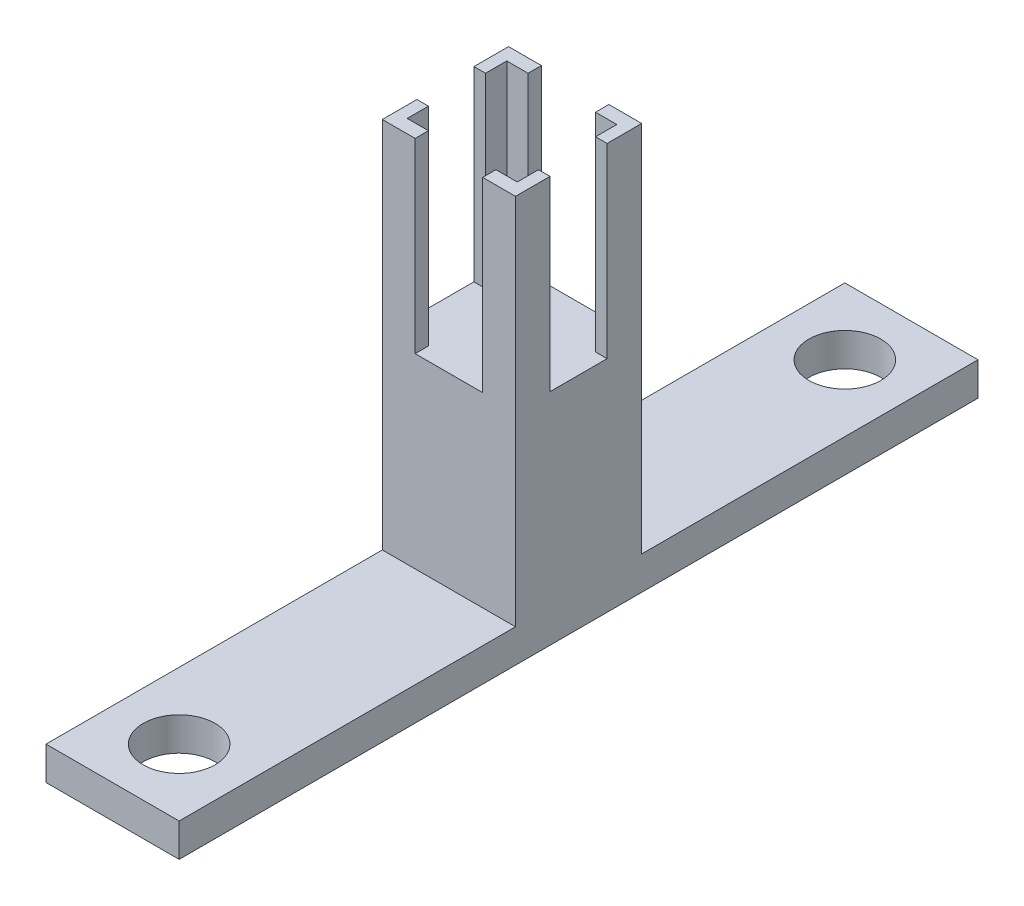
SolidWorks part; units mm, degrees
ref_plane "Front Plane" through (0, 0, 0) normal (0, 0, 1) x (1, 0, 0)
ref_plane "Top Plane" through (0, 0, 0) normal (0, 1, 0) x (1, 0, 0)
ref_plane "Right Plane" through (0, 0, 0) normal (1, 0, 0) x (0, 0, -1)
sketch "Sketch1" plane through (0, 0, 0) normal (0, 1, 0) x (1, 0, 0)
  line L0 (-5.25, 4.75) -> (-5.25, 2.718)
  line L1 (-5.25, -4.75) -> (5.25, -4.75) construction
  line L2 (-5.25, -4.75) -> (-5.25, 4.75) construction
  line L3 (-5.25, 4.75) -> (5.25, 4.75) construction
  line L4 (5.25, -4.75) -> (5.25, 4.75) construction
  line L5 (-5.25, -4.75) -> (5.25, 4.75) construction
  line L6 (-5.25, 4.75) -> (5.25, -4.75) construction
  line L7 (-5.25, 2.718) -> (-6.52, 2.718)
  line L8 (-6.52, 2.718) -> (-6.52, 6.02)
  line L9 (-6.52, 6.02) -> (-3.218, 6.02)
  line L10 (-3.218, 6.02) -> (-3.218, 4.75)
  line L11 (-3.218, 4.75) -> (-5.25, 4.75)
  line L12 (0, 4.75) -> (0, -4.75) construction
  line L13 (-5.25, 0) -> (5.25, 0) construction
  line L14 (6.52, 2.718) -> (6.52, 6.02)
  line L15 (5.25, 2.718) -> (6.52, 2.718)
  line L16 (5.25, 4.75) -> (5.25, 2.718)
  line L17 (3.218, 4.75) -> (5.25, 4.75)
  line L18 (3.218, 6.02) -> (3.218, 4.75)
  line L19 (6.52, 6.02) -> (3.218, 6.02)
  line L20 (5.25, -2.718) -> (6.52, -2.718)
  line L21 (5.25, -4.75) -> (5.25, -2.718)
  line L22 (3.218, -4.75) -> (5.25, -4.75)
  line L23 (3.218, -6.02) -> (3.218, -4.75)
  line L24 (6.52, -6.02) -> (3.218, -6.02)
  line L25 (6.52, -2.718) -> (6.52, -6.02)
  line L26 (-5.25, -2.718) -> (-6.52, -2.718)
  line L27 (-5.25, -4.75) -> (-5.25, -2.718)
  line L28 (-3.218, -4.75) -> (-5.25, -4.75)
  line L29 (-3.218, -6.02) -> (-3.218, -4.75)
  line L30 (-6.52, -6.02) -> (-3.218, -6.02)
  line L31 (-6.52, -2.718) -> (-6.52, -6.02)
  point P0 (0, 0)
  dimension "D1" = 10.5
  dimension "D2" = 9.5
  dimension "D3" = 1.27
  dimension "D4" = 2.032
extrude "Boss-Extrude1" add sketch "Sketch1" along normal blind 17.78
sketch "Sketch2" plane through (0, 0, 0) normal (0, -1, 0) x (-1, 0, 0)
  line L1 (6.52, -6.02) -> (-6.52, -6.02)
  line L2 (6.52, -6.02) -> (6.52, 6.02)
  line L3 (6.52, 6.02) -> (-6.52, 6.02)
  line L4 (-6.52, -6.02) -> (-6.52, 6.02)
extrude "Boss-Extrude2" add sketch "Sketch2" along normal blind 17.78
sketch "Sketch3" plane through (0, -17.78, 0) normal (0, -1, 0) x (-1, 0, 0)
  line L0 (0, 0) -> (6.35, 0) construction
  line L1 (-6.35, -38.1) -> (6.35, -38.1)
  line L2 (-6.35, -38.1) -> (-6.35, 38.1)
  line L3 (-6.35, 38.1) -> (6.35, 38.1)
  line L4 (6.35, -38.1) -> (6.35, 38.1)
  line L5 (-6.35, -38.1) -> (6.35, 38.1) construction
  line L6 (-6.35, 38.1) -> (6.35, -38.1) construction
  circle A0 centre (0, 31.75) radius 3.429
  circle A1 centre (0, -31.75) radius 3.429
  point P0 (0, 0)
  dimension "D2" = 6.858
  dimension "D1" = 12.7
  dimension "D3" = 31.75
  dimension "D4" = 76.2
extrude "Boss-Extrude3" add sketch "Sketch3" along normal blind 3.175
sketch "Sketch4" plane through (0, -20.955, 0) normal (0, -1, 0) x (1, 0, 0)
  line L4 (-6.35, 38.1) -> (-6.35, -38.1)
  line L5 (-6.35, -38.1) -> (6.35, -38.1)
  line L6 (6.35, -38.1) -> (6.35, 38.1)
  line L7 (6.35, 38.1) -> (-6.35, 38.1)
  line L8 (-6.35, 38.1) -> (-6.35, -38.1)
  line L9 (-6.35, -38.1) -> (6.35, -38.1)
  line L10 (6.35, -38.1) -> (6.35, 38.1)
  line L11 (6.35, 38.1) -> (-6.35, 38.1)
  dimension "D1" = 0
extrude "Cut-Extrude2" cut sketch "Sketch4" against normal through all flip side to cut
